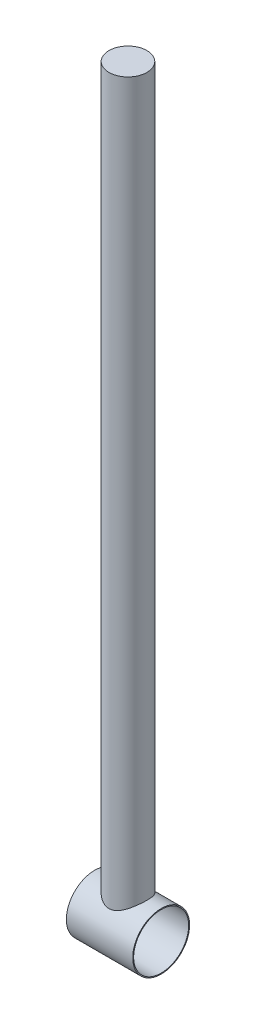
SolidWorks part; units mm, degrees
material "Chrome Stainless Steel"
ref_plane "Plano frontal" through (0, 0, 0) normal (0, 0, 1) x (1, 0, 0)
ref_plane "Plano superior" through (0, 0, 0) normal (0, 1, 0) x (1, 0, 0)
ref_plane "Plano direito" through (0, 0, 0) normal (1, 0, 0) x (0, 0, -1)
sketch "Sketch2" plane through (0, 0, 0) normal (1, 0, 0) x (0, 0, -1)
  circle A0 centre (0, 0) radius 30
  circle A1 centre (0, 0) radius 29
  dimension "D1" = 60
  dimension "D2" = 1
extrude "Boss-Extrude3" add sketch "Sketch2" along normal mid plane 70
sketch "Sketch1" plane through (0, 0, 0) normal (0, 1, 0) x (1, 0, 0)
  circle A0 centre (0, 0) radius 20
  dimension "D1" = 40
extrude "Boss-Extrude4" add sketch "Sketch1" against normal up to surface (763.6393 mm away) from offset 786
